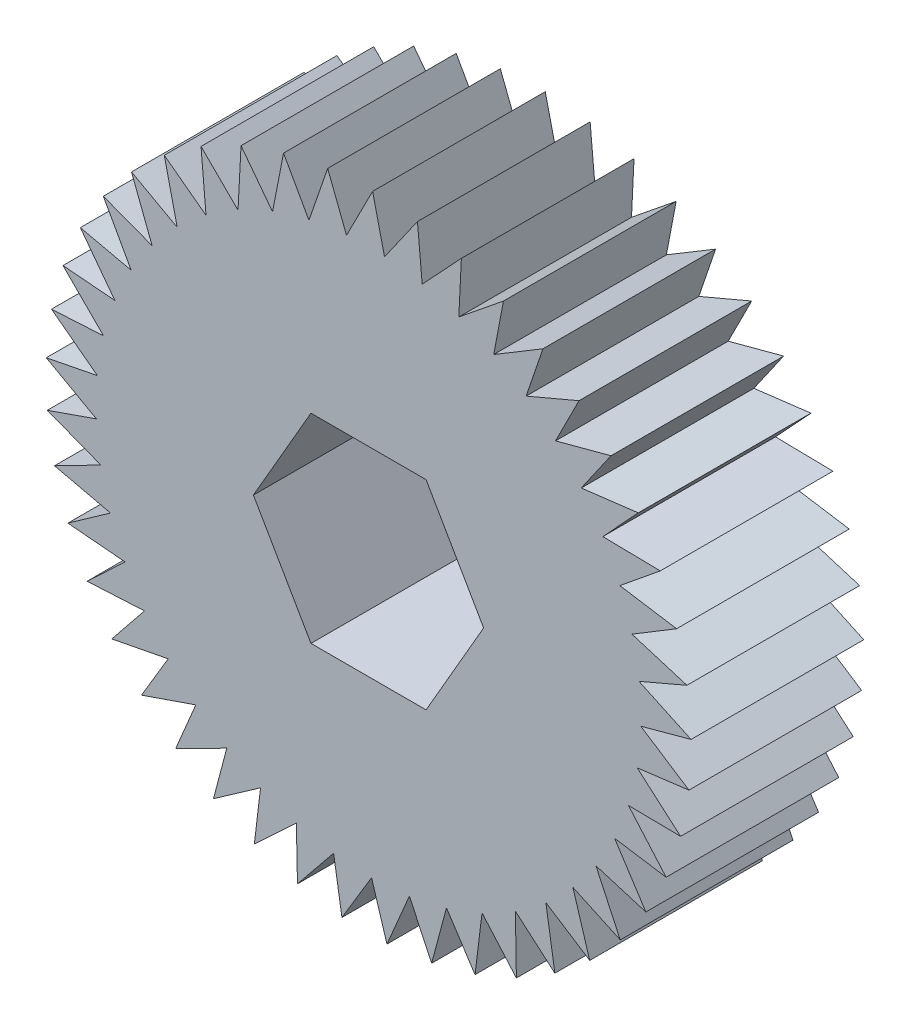
SolidWorks part; units mm, degrees
ref_plane "Piano frontale" through (0, 0, 0) normal (0, 0, 1) x (1, 0, 0)
ref_plane "Piano superiore" through (0, 0, 0) normal (0, 1, 0) x (1, 0, 0)
ref_plane "Piano destro" through (0, 0, 0) normal (1, 0, 0) x (0, 0, -1)
sketch "Schizzo1" plane through (0, 0, 0) normal (0, 0, 1) x (1, 0, 0)
  line L1 (10, 0) -> (5, 8.6603)
  line L2 (5, 8.6603) -> (-5, 8.6603)
  line L3 (-5, 8.6603) -> (-10, 0)
  line L4 (-10, 0) -> (-5, -8.6603)
  line L5 (-5, -8.6603) -> (5, -8.6603)
  line L6 (5, -8.6603) -> (10, 0)
  circle A0 centre (0, 0) radius 34.641
  circle A1 centre (0, 0) radius 8.6603 construction
  dimension "D1" = 10
extrude "Estrusione-Estrusione1" add sketch "Schizzo1" along normal mid plane 15
sketch "Schizzo2" plane through (0, 0, 7.5) normal (0, 0, 1) x (1, 0, 0)
  line L0 (-6.5513, 35.5342) -> (-1.9115, 23.5801)
  line L1 (-1.9115, 23.5801) -> (5.3482, 37.8268)
  line L2 (5.3482, 37.8268) -> (-6.5513, 35.5342)
extrude "Taglio-Estrusione1" cut sketch "Schizzo2" against normal through all
pattern_circular "RipetizioneCircolare1" count 45 over 360 about axis through (0, 0, 0) along (0, 0, 1) of "Taglio-Estrusione1"
